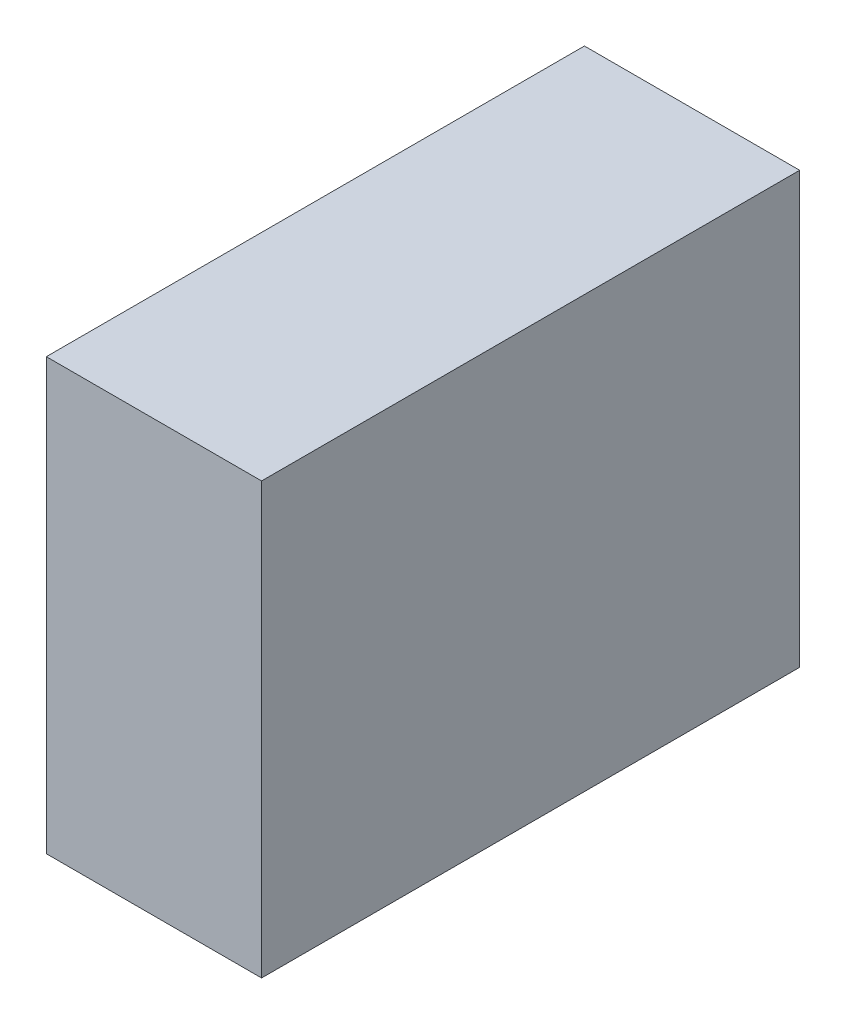
SolidWorks part; units mm, degrees
ref_plane "Front Plane" through (0, 0, 0) normal (0, 0, 1) x (1, 0, 0)
ref_plane "Top Plane" through (0, 0, 0) normal (0, 1, 0) x (1, 0, 0)
ref_plane "Right Plane" through (0, 0, 0) normal (1, 0, 0) x (0, 0, -1)
sketch "Sketch1" plane through (0, 0, 0) normal (0, 0, 1) x (1, 0, 0)
  line L1 (-2, 4) -> (2, 4)
  line L2 (-2, 4) -> (-2, -4)
  line L3 (-2, -4) -> (2, -4)
  line L4 (2, 4) -> (2, -4)
  line L5 (-2, 4) -> (2, -4) construction
  line L6 (-2, -4) -> (2, 4) construction
  point P0 (0, 0)
  dimension "D1" = 4
  dimension "D2" = 8
extrude "Boss-Extrude1" add sketch "Sketch1" along normal blind 10
